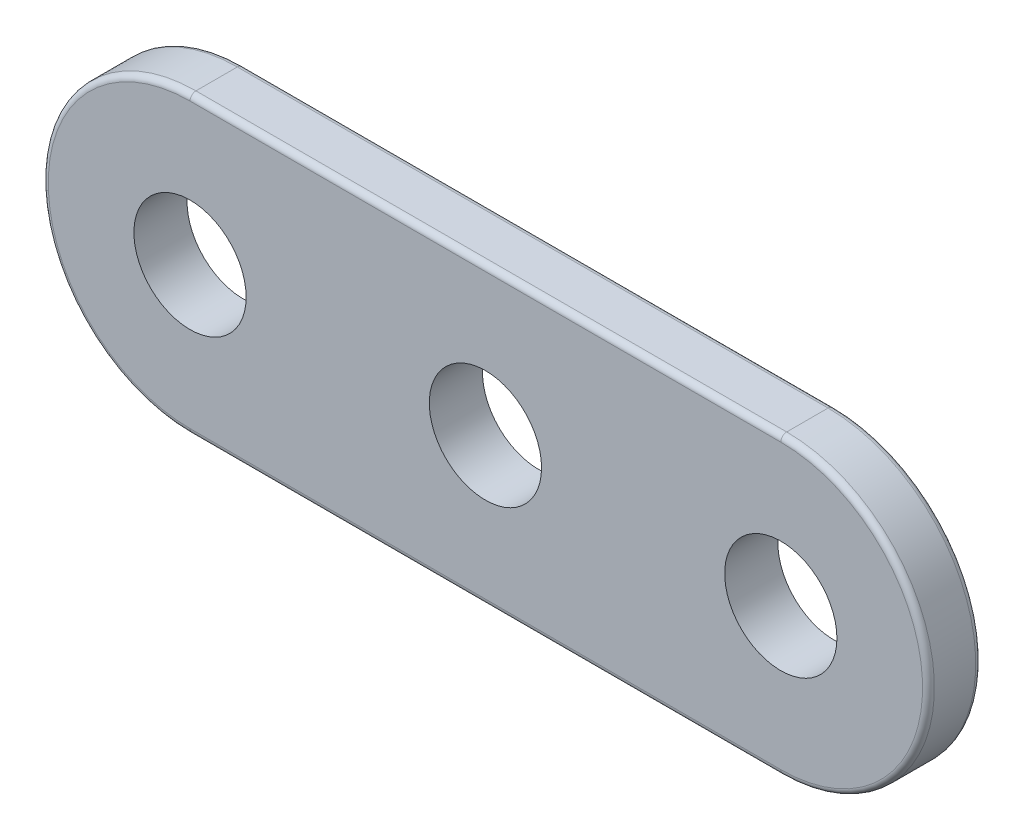
SolidWorks part; units mm, degrees
material "AISI 304"
ref_plane "Front Plane" through (0, 0, 0) normal (0, 0, 1) x (1, 0, 0)
ref_plane "Top Plane" through (0, 0, 0) normal (0, 1, 0) x (1, 0, 0)
ref_plane "Right Plane" through (0, 0, 0) normal (1, 0, 0) x (0, 0, -1)
sketch "Sketch1" plane through (0, 0, 0) normal (0, 0, 1) x (1, 0, 0)
  line L0 (-12.7, 0) -> (12.7, 0) construction
  line L1 (-12.7, 6.35) -> (12.7, 6.35)
  line L2 (-12.7, -6.35) -> (12.7, -6.35)
  arc A0 (-12.7, 6.35) -> (-12.7, -6.35) centre (-12.7, 0) ccw
  arc A1 (12.7, -6.35) -> (12.7, 6.35) centre (12.7, 0) ccw
  point P3 (0, 0)
  dimension "D2" = 6.35
  dimension "D1" = 25.4
extrude "Extrude1" add sketch "Sketch1" along normal blind 2.286
sketch "Sketch2" plane through (0, 0, 2.286) normal (0, 0, 1) x (1, 0, 0)
  circle A0 centre (-12.7, 0) radius 2.413
  dimension "D1" = 4.826
extrude "Extrude2" cut sketch "Sketch2" against normal through all
pattern_linear "LPattern1" count 3 spacing 12.7 along (1, 0, 0) of "Extrude2"
fillet "Fillet1" radius 0.254 8 edges at (19.05, 0, 0) (0, -6.35, 0) (-19.05, 0, 0) (19.05, 0, 2.286) (0, -6.35, 2.286) (-19.05, 0, 2.286) (0, 6.35, 0) (0, 6.35, 2.286)
